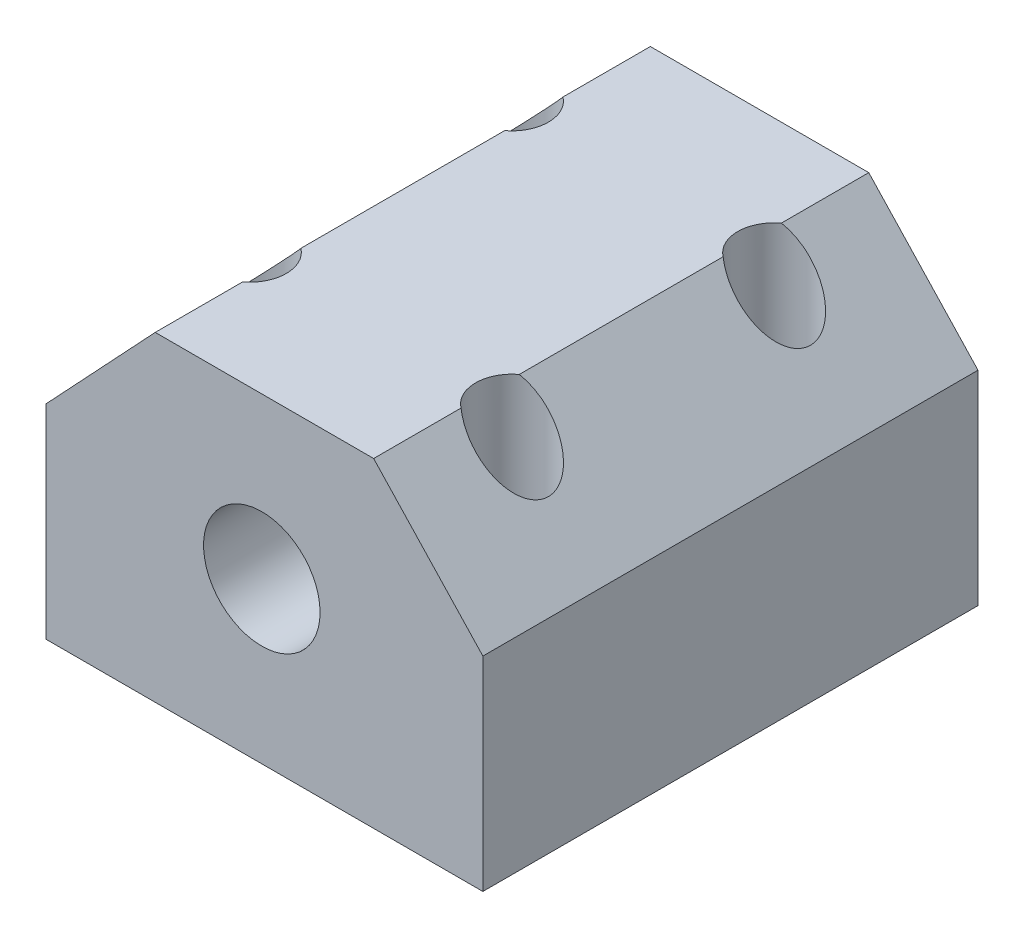
SolidWorks part; units mm, degrees
ref_plane "Front Plane" through (0, 0, 0) normal (0, 0, 1) x (1, 0, 0)
ref_plane "Top Plane" through (0, 0, 0) normal (0, 1, 0) x (1, 0, 0)
ref_plane "Right Plane" through (0, 0, 0) normal (1, 0, 0) x (0, 0, -1)
sketch "Sketch1" plane through (0, 0, 0) normal (0, 1, 0) x (1, 0, 0)
  line L1 (0, 0) -> (30, 0)
  line L2 (0, 0) -> (0, 34)
  line L3 (0, 34) -> (30, 34)
  line L4 (30, 0) -> (30, 34)
  dimension "D1" = 34
  dimension "D2" = 30
extrude "Boss-Extrude1" add sketch "Sketch1" along normal blind 22
sketch "Sketch2" plane through (0, 0, 0) normal (0, 0, 1) x (1, 0, 0)
  line L0 (0, 0) -> (30, 0) construction
  line L1 (0, 14) -> (7.5, 22)
  line L2 (0, 22) -> (0, 0) construction
  line L3 (0, 22) -> (30, 22) construction
  line L4 (7.5, 22) -> (0, 22)
  line L5 (0, 22) -> (0, 14)
  line L6 (30, 14) -> (22.5, 22)
  line L7 (30, 22) -> (30, 0) construction
  line L8 (22.5, 22) -> (30, 22)
  line L9 (30, 22) -> (30, 14)
  circle A0 centre (14.8206, 11) radius 4
  dimension "D1" = 8
  dimension "D2" = 11
  dimension "D4" = 8
  dimension "D5" = 8
  dimension "D6" = 15
  dimension "D7" = 7.5
extrude "Cut-Extrude1" cut sketch "Sketch2" against normal up to next
sketch "Sketch3" plane through (0, 0, 0) normal (0, -1, 0) x (1, 0, 0)
  line L0 (30, 0) -> (30, -34) construction
  line L1 (30, -34) -> (0, -34) construction
  circle A0 centre (6, -8) radius 2.5
  circle A1 centre (24, -8) radius 2.5
  circle A2 centre (24, -26) radius 2.5
  circle A3 centre (6, -26) radius 2.5
  dimension "D1" = 5
  dimension "D2" = 5
  dimension "D3" = 5
  dimension "D4" = 5
  dimension "D5" = 0
  dimension "D6" = 0
  dimension "D7" = 0
  dimension "D8" = 0
  dimension "D9" = 18
  dimension "D10" = 18
  dimension "D11" = 6
  dimension "D12" = 8
extrude "Cut-Extrude2" cut sketch "Sketch3" against normal blind 22
